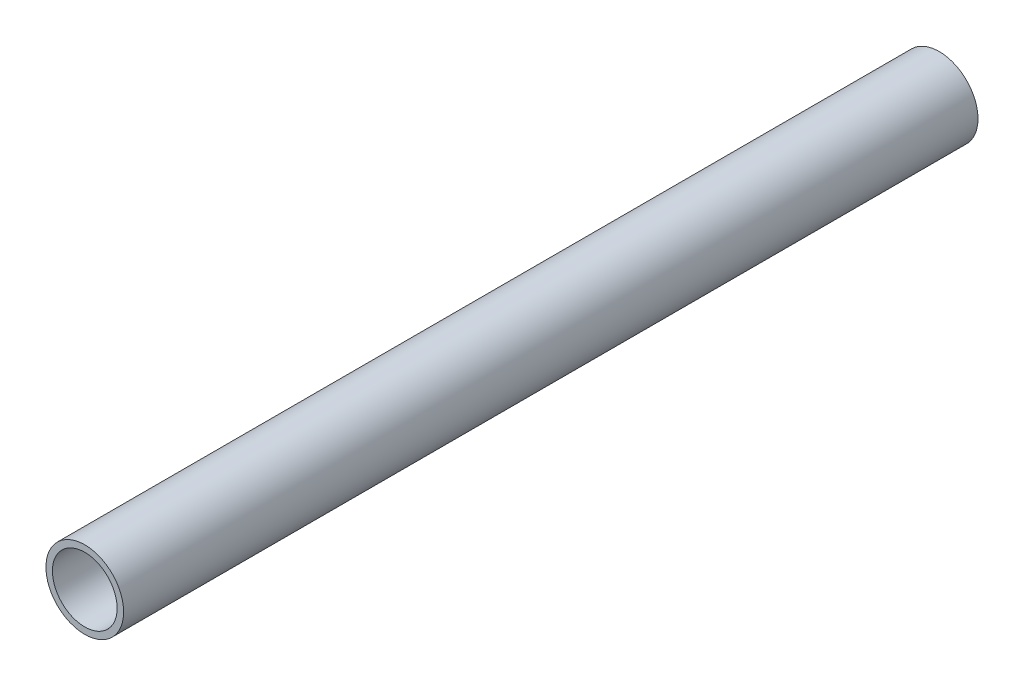
SolidWorks part; units mm, degrees
ref_plane "Front Plane" through (0, 0, 0) normal (0, 0, 1) x (1, 0, 0)
ref_plane "Top Plane" through (0, 0, 0) normal (0, 1, 0) x (1, 0, 0)
ref_plane "Right Plane" through (0, 0, 0) normal (1, 0, 0) x (0, 0, -1)
sketch "Sketch1" plane through (0, 0, 0) normal (0, 0, 1) x (1, 0, 0)
  circle A0 centre (-20.2566, 12.3556) radius 4.7625
  circle A1 centre (-20.2566, 12.3556) radius 3.2004
  dimension "D1" = 9.525
  dimension "D2" = 6.4008
extrude "Boss-Extrude1" add sketch "Sketch1" along normal blind 104.775
hole_wizard "3/8-16 Tapped Hole2" positions "Sketch9" profile "Sketch8" tap size "3/8-16" standard "ANSI Inch"
sketch "Sketch9" plane through (0, 0, 104.775) normal (0, 0, 1) x (1, 0, 0)
  point P0 (-20.2566, 12.3556)
sketch "Sketch8" plane through (-20.2566, 12.3556, 104.775) normal (1, 0, 0) x (0, -1, 0)
  line L0 (0, 0) -> (0, 26.2607)
  line L1 (0, 26.2607) -> (3.9687, 23.876)
  line L2 (3.9687, 23.876) -> (3.9687, 0)
  line L5 (3.9687, 0) -> (0, 0)
  line L10 (0, 26.2607) -> (-3.9687, 23.876) construction
  line L11 (0, -6.35) -> (0, 107.95) construction
  dimension "Tap Drill Dia." = 7.9375
  dimension "Tap Drill Depth" = 23.876
  dimension "Drill Angle" = 118
cosmetic thread "Hole Thread2" parameters "D1"=19.05, "D2"=9.525
